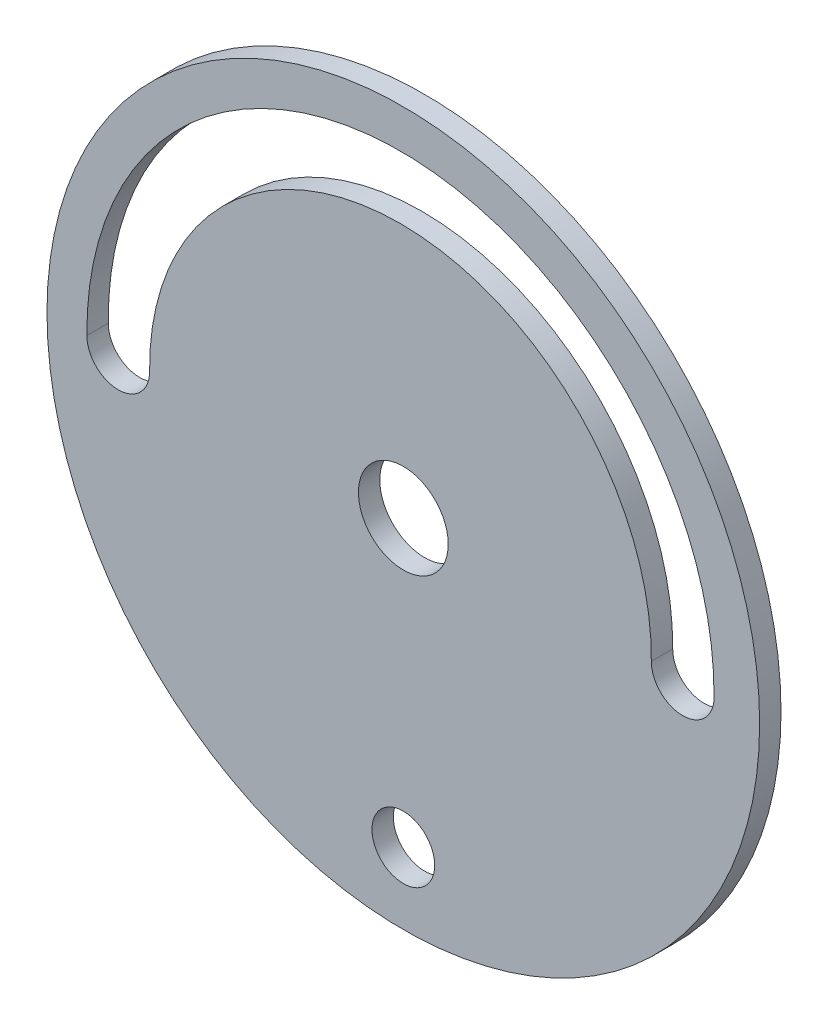
SolidWorks part; units mm, degrees
ref_plane "Front Plane" through (0, 0, 0) normal (0, 0, 1) x (1, 0, 0)
ref_plane "Top Plane" through (0, 0, 0) normal (0, 1, 0) x (1, 0, 0)
ref_plane "Right Plane" through (0, 0, 0) normal (1, 0, 0) x (0, 0, -1)
sketch "Sketch1" plane through (0, 0, 0) normal (0, 0, 1) x (1, 0, 0)
  line L0 (-27.0565, 7.3948) -> (22.9435, 7.3948) construction
  line L1 (-2.2565, 25.1948) -> (-2.2565, 29.5948) construction
  circle A0 centre (-2.0565, 7.3948) radius 25
  circle A2 centre (-2.0565, -12.6052) radius 2.2
  arc A3 (19.7435, 7.3948) -> (-24.2565, 7.3948) centre (-2.2565, 7.5939) ccw
  arc A4 (15.3435, 7.3948) -> (-19.8565, 7.3948) centre (-2.2565, 7.5937) ccw
  arc A5 (19.7435, 7.3948) -> (15.3435, 7.3948) centre (17.5435, 7.3948) cw
  arc A6 (-24.2565, 7.3948) -> (-19.8565, 7.3948) centre (-22.0565, 7.3948) ccw
  circle A7 centre (-2.0565, 7.3948) radius 3.15
  point P2 (-2.2565, 27.3948)
  dimension "D1" = 4.4
  dimension "D2" = 50
  dimension "D4" = 6.3
  dimension "D3" = 20
  dimension "D5" = 4.4
  dimension "D6" = 20
extrude "Boss-Extrude1" add sketch "Sketch1" along normal blind 1.5
